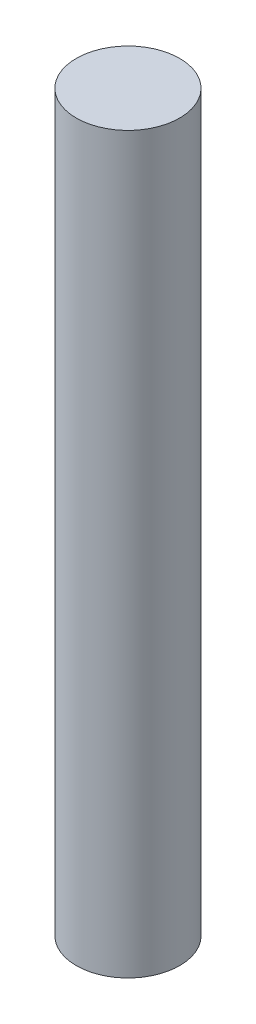
SolidWorks part; units mm, degrees
ref_plane "Front Plane" through (0, 0, 0) normal (0, 0, 1) x (1, 0, 0)
ref_plane "Top Plane" through (0, 0, 0) normal (0, 1, 0) x (1, 0, 0)
ref_plane "Right Plane" through (0, 0, 0) normal (1, 0, 0) x (0, 0, -1)
sketch "Sketch1" plane through (0, 0, 0) normal (0, 1, 0) x (1, 0, 0)
  circle A0 centre (0, 0) radius 0.5
  dimension "D1" = 1
extrude "Boss-Extrude1" add sketch "Sketch1" along normal blind 7.1
